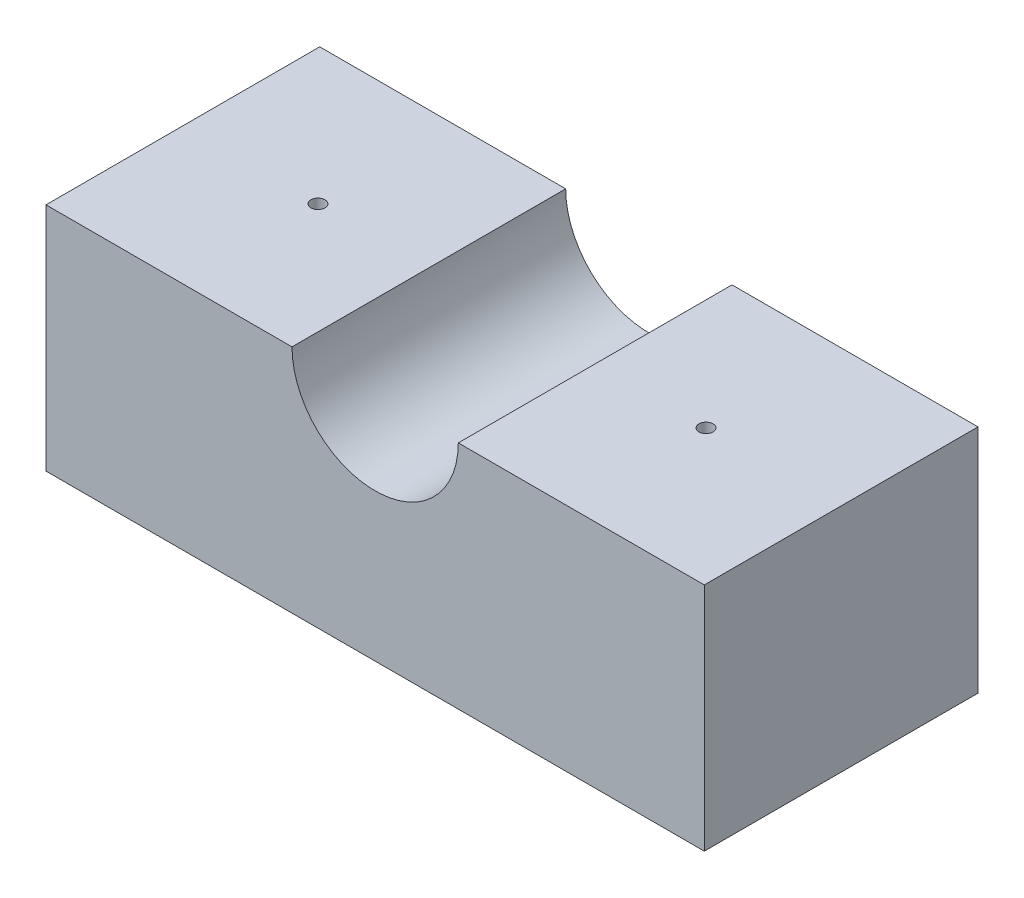
SolidWorks part; units mm, degrees
material "Custom Plastic"
ref_plane "Front Plane" through (0, 0, 0) normal (0, 0, 1) x (1, 0, 0)
ref_plane "Top Plane" through (0, 0, 0) normal (0, 1, 0) x (1, 0, 0)
ref_plane "Right Plane" through (0, 0, 0) normal (1, 0, 0) x (0, 0, -1)
sketch "Sketch2" plane through (0, 0, 0) normal (0, 1, 0) x (1, 0, 0)
  line L0 (-11.873, 4.9365) -> (11.873, 4.9365)
  line L1 (11.873, 4.9365) -> (11.873, -4.9365)
  line L2 (11.873, -4.9365) -> (-11.873, -4.9365)
  line L3 (-11.873, -4.9365) -> (-11.873, 4.9365)
  dimension "D1" = 11.873
  dimension "D2" = 4.9365
  dimension "D3" = 4.9365
  dimension "D4" = 11.873
extrude "Boss-Extrude1" add sketch "Sketch2" along normal blind 8.3185 contours L0 L1 L2 L3
sketch "Sketch3" plane through (0, 0, 4.9365) normal (0, 0, 1) x (1, 0, 0)
  line L0 (11.873, 8.3185) -> (-11.873, 8.3185) construction
  circle A0 centre (0, 8.3185) radius 2.9997
extrude "Cut-Extrude1" cut sketch "Sketch3" against normal through all contours A0
sketch "Sketch4" plane through (0, 8.3185, 0) normal (0, 1, 0) x (1, 0, 0)
  circle A0 centre (-7, 0) radius 0.254
  circle A1 centre (7, 0) radius 0.254
  point P7 (0, 0)
extrude "Cut-Extrude2" cut sketch "Sketch4" against normal blind 2.54
